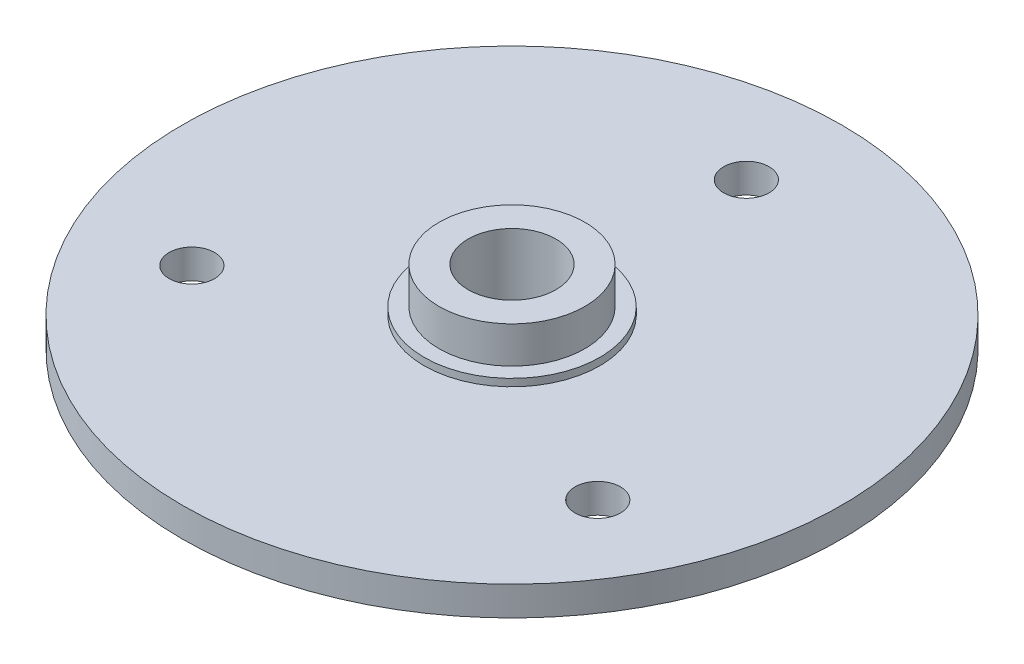
SolidWorks part; units mm, degrees
ref_plane "正面" through (0, 0, 0) normal (0, 0, 1) x (1, 0, 0)
ref_plane "平面" through (0, 0, 0) normal (0, 1, 0) x (1, 0, 0)
ref_plane "右側面" through (0, 0, 0) normal (1, 0, 0) x (0, 0, -1)
sketch "ｽｹｯﾁ1" plane through (0, 0, 0) normal (0, 1, 0) x (1, 0, 0)
  line L0 (0, 0) -> (0, 16) construction
  line L1 (-13.8564, -8) -> (0, 0) construction
  line L2 (0, 0) -> (13.8564, -8) construction
  circle A0 centre (0, 0) radius 22.5
  circle A1 centre (0, 16) radius 1.55
  circle A2 centre (13.8564, -8) radius 1.55
  circle A3 centre (-13.8564, -8) radius 1.55
  dimension "D1" = 45
  dimension "D2" = 16
  dimension "D3" = 3.1
  dimension "D4" = 3
extrude "ﾎﾞｽ - 押し出し1" add sketch "ｽｹｯﾁ1" along normal blind 2
sketch "ｽｹｯﾁ2" plane through (0, 2, 0) normal (0, 1, 0) x (1, 0, 0)
  circle A0 centre (0, 0) radius 4.98
  dimension "D1" = 9.96
extrude "ﾎﾞｽ - 押し出し2" add sketch "ｽｹｯﾁ2" along normal blind 3
sketch "ｽｹｯﾁ3" plane through (0, 2, 0) normal (0, 1, 0) x (1, 0, 0)
  circle A0 centre (0, 0) radius 6
  dimension "D1" = 12
extrude "ﾎﾞｽ - 押し出し3" add sketch "ｽｹｯﾁ3" along normal blind 0.5
sketch "ｽｹｯﾁ4" plane through (0, 5, 0) normal (0, 1, 0) x (1, 0, 0)
  circle A0 centre (0, 0) radius 3
  dimension "D1" = 6
extrude "ｶｯﾄ - 押し出し1" cut sketch "ｽｹｯﾁ4" against normal through all
